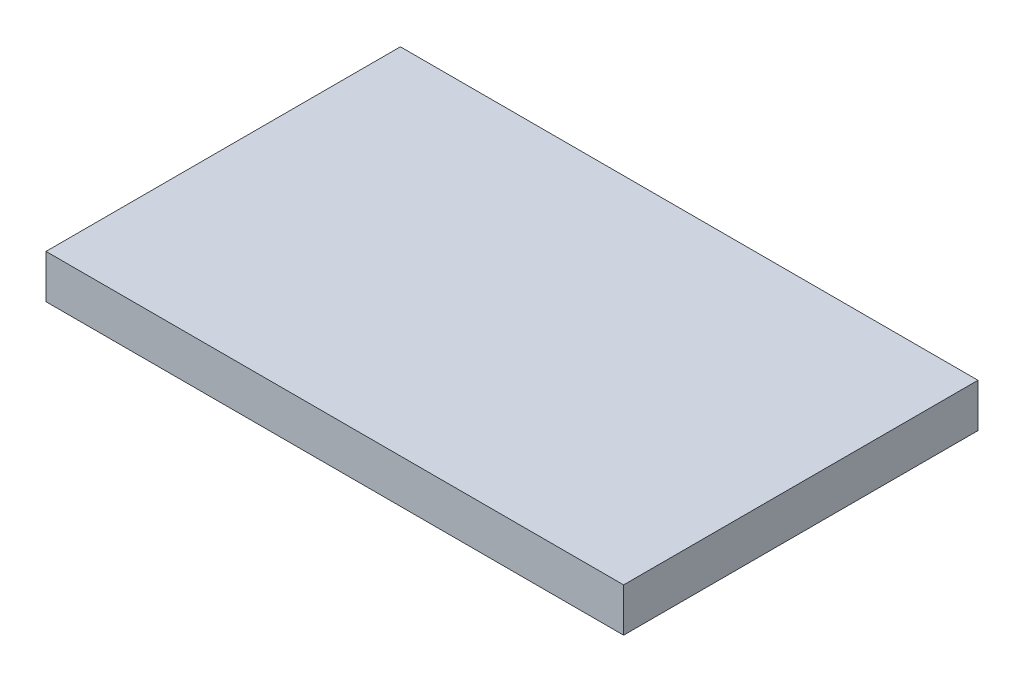
SolidWorks part; units mm, degrees
material "Plain Carbon Steel"
ref_plane "Front Plane" through (0, 0, 0) normal (0, 0, 1) x (1, 0, 0)
ref_plane "Top Plane" through (0, 0, 0) normal (0, 1, 0) x (1, 0, 0)
ref_plane "Right Plane" through (0, 0, 0) normal (1, 0, 0) x (0, 0, -1)
sketch "Sketch1" plane through (0, 0, 0) normal (0, 1, 0) x (1, 0, 0)
  line L1 (0, 0) -> (41.4, 0)
  line L2 (0, 0) -> (0, 25.4)
  line L3 (0, 25.4) -> (41.4, 25.4)
  line L4 (41.4, 0) -> (41.4, 25.4)
  dimension "D1" = 41.4
  dimension "D2" = 25.4
extrude "Boss-Extrude1" add sketch "Sketch1" along normal blind 3.125
